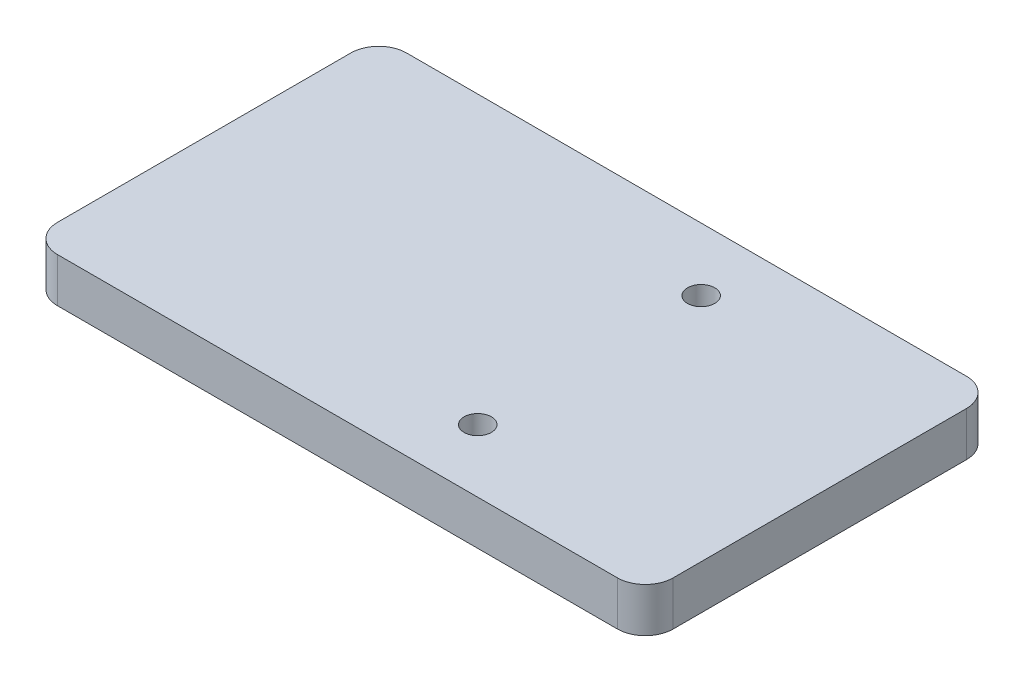
SolidWorks part; units mm, degrees
ref_plane "Front Plane" through (0, 0, 0) normal (0, 0, 1) x (1, 0, 0)
ref_plane "Top Plane" through (0, 0, 0) normal (0, 1, 0) x (1, 0, 0)
ref_plane "Right Plane" through (0, 0, 0) normal (1, 0, 0) x (0, 0, -1)
sketch "Sketch1" plane through (0, 0, 0) normal (0, 1, 0) x (1, 0, 0)
  line L0 (-44.09, 0) -> (44.09, 0) construction
  line L1 (-44.09, 25) -> (44.09, 25)
  line L2 (-44.09, 25) -> (-44.09, -25)
  line L3 (-44.09, -25) -> (44.09, -25)
  line L4 (44.09, 25) -> (44.09, -25)
  line L5 (-44.09, 25) -> (44.09, -25) construction
  line L6 (-44.09, -25) -> (44.09, 25) construction
  circle A0 centre (11.09, 16) radius 1.95
  circle A1 centre (11.09, -16) radius 1.95
  point P0 (0, 0)
  dimension "D1" = 3.9
  dimension "D2" = 16
  dimension "D3" = 16
  dimension "D4" = 50
  dimension "D5" = 88.18
  dimension "D6" = 33
extrude "Boss-Extrude1" add sketch "Sketch1" along normal blind 6.35
fillet "Fillet1" radius 4 4 edges at (-44.09, 3.175, 25) (-44.09, 3.175, -25) (44.09, 3.175, 25) (44.09, 3.175, -25)
